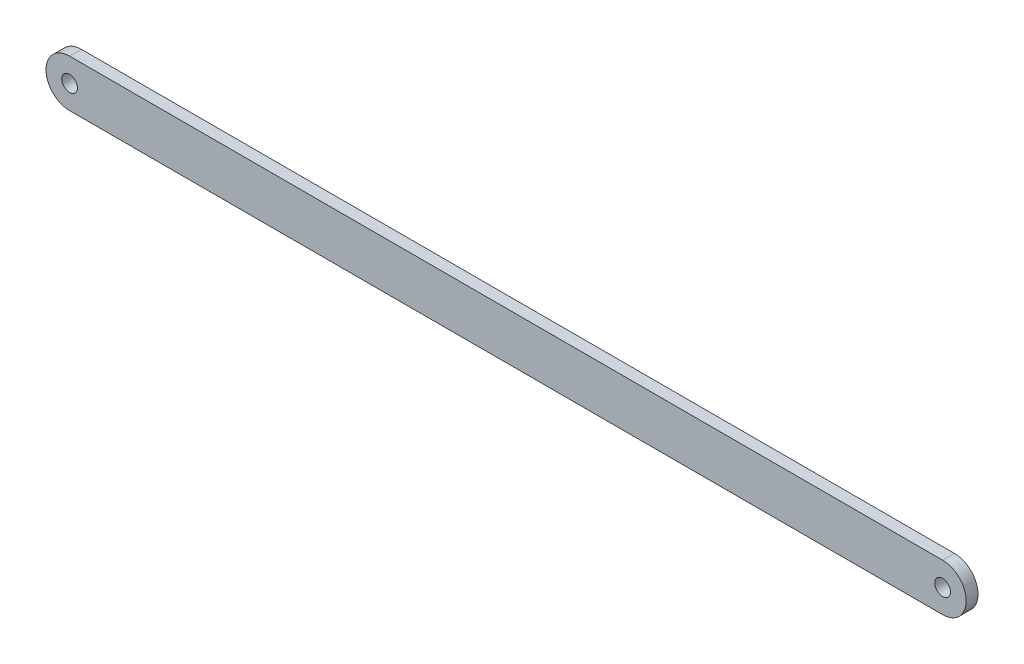
SolidWorks part; units mm, degrees
ref_plane "Front Plane" through (0, 0, 0) normal (0, 0, 1) x (1, 0, 0)
ref_plane "Top Plane" through (0, 0, 0) normal (0, 1, 0) x (1, 0, 0)
ref_plane "Right Plane" through (0, 0, 0) normal (1, 0, 0) x (0, 0, -1)
sketch "Sketch1" plane through (0, 0, 0) normal (0, 0, 1) x (1, 0, 0)
  line L0 (-35.3127, 0) -> (186.6873, 0) construction
  line L1 (-35.3127, 6) -> (186.6873, 6)
  line L2 (-35.3127, -6) -> (186.6873, -6)
  arc A0 (-35.3127, 6) -> (-35.3127, -6) centre (-35.3127, 0) ccw
  arc A1 (186.6873, -6) -> (186.6873, 6) centre (186.6873, 0) ccw
  circle A2 centre (-35.3127, 0) radius 2
  circle A3 centre (186.6873, 0) radius 2
  point P3 (75.6873, 0)
  dimension "D3" = 4
  dimension "D4" = 4
  dimension "D1" = 222
  dimension "D2" = 12
extrude "Boss-Extrude3" add sketch "Sketch1" along normal blind 3
